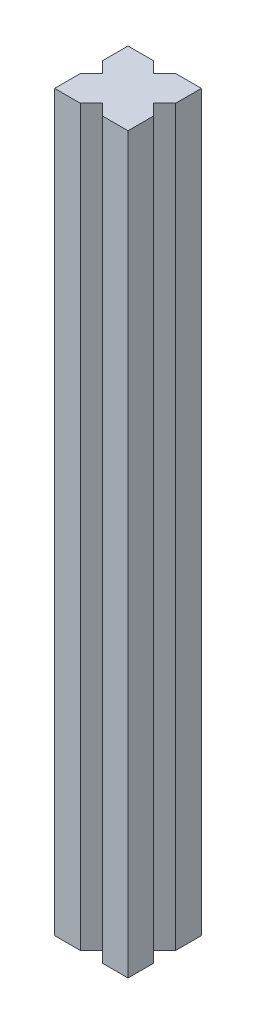
SolidWorks part; units mm, degrees
ref_plane "Front" through (0, 0, 0) normal (0, 0, 1) x (1, 0, 0)
ref_plane "Top" through (0, 0, 0) normal (0, 1, 0) x (1, 0, 0)
ref_plane "Right" through (0, 0, 0) normal (1, 0, 0) x (0, 0, -1)
sketch "Skizze1" plane through (0, 0, 0) normal (0, 1, 0) x (1, 0, 0)
  line L1 (0, 0) -> (20, 0)
  line L2 (0, 0) -> (0, 20)
  line L3 (0, 20) -> (20, 20)
  line L4 (20, 0) -> (20, 20)
  dimension "D1" = 20
extrude "Aufsatz-Linear austragen1" add sketch "Skizze1" along normal blind 200
sketch "Skizze2" plane through (0, 200, 0) normal (0, 1, 0) x (1, 0, 0)
  line L0 (10, 20) -> (10, 0) construction
  line L1 (0, 10) -> (20, 10) construction
  line L2 (7, 20) -> (10, 17)
  line L3 (13, 20) -> (10, 17)
  line L4 (10, 10) -> (20, 20) construction
  line L5 (7, 20) -> (13, 20)
  line L6 (20, 13) -> (17, 10)
  line L7 (20, 7) -> (17, 10)
  line L8 (20, 7) -> (20, 13)
  line L9 (0, 7) -> (0, 13)
  line L10 (0, 7) -> (3, 10)
  line L11 (0, 13) -> (3, 10)
  line L12 (7, 0) -> (13, 0)
  line L13 (13, 0) -> (10, 3)
  line L14 (7, 0) -> (10, 3)
  line L15 (20, 20) -> (0, 20) construction
  line L16 (20, 0) -> (20, 20) construction
  line L17 (0, 0) -> (20, 0) construction
  dimension "D1" = 3
  dimension "D2" = 3
extrude "Schnitt-Linear austragen1" cut sketch "Skizze2" against normal through all
ref_plane "Ebene1" through (10, 0, 0) normal (1, 0, 0) x (0, 0, -1)
